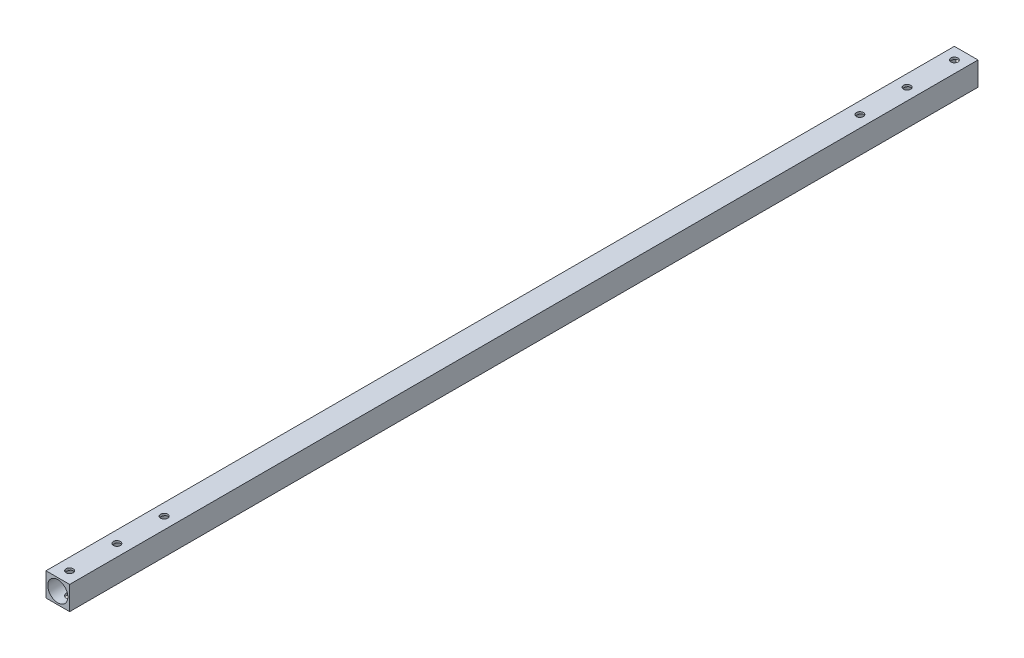
SolidWorks part; units mm, degrees
material "Thornel VCB-20 Carbon Cloth"
ref_plane "Front Plane" through (0, 0, 0) normal (0, 0, 1) x (1, 0, 0)
ref_plane "Top Plane" through (0, 0, 0) normal (0, 1, 0) x (1, 0, 0)
ref_plane "Right Plane" through (0, 0, 0) normal (1, 0, 0) x (0, 0, -1)
sketch "Sketch1" plane through (0, 0, 0) normal (0, 0, 1) x (1, 0, 0)
  line L1 (-5, -5) -> (5, -5)
  line L2 (-5, -5) -> (-5, 5)
  line L3 (-5, 5) -> (5, 5)
  line L4 (5, -5) -> (5, 5)
  line L5 (-5, -5) -> (5, 5) construction
  line L6 (-5, 5) -> (5, -5) construction
  circle A0 centre (0, 0) radius 4.25
  point P0 (0, 0)
  dimension "D3" = 8.5
  dimension "D1" = 10
  dimension "D2" = 10
extrude "Boss-Extrude1" add sketch "Sketch1" along normal blind 384.4
sketch "Sketch2" plane through (0, 5, 0) normal (0, 1, 0) x (1, 0, 0)
  line L0 (0, 0) -> (0, -5) construction
  line L1 (0, -5) -> (0, -25) construction
  line L2 (0, -25) -> (0, -45) construction
  line L3 (0, -384.4) -> (0, -379.4) construction
  line L4 (5, -384.4) -> (-5, -384.4) construction
  line L5 (0, -379.4) -> (0, -359.4) construction
  line L6 (0, -359.4) -> (0, -339.4) construction
  circle A0 centre (0, -5) radius 1.5
  circle A1 centre (0, -25) radius 1.5
  circle A2 centre (0, -45) radius 1.5
  circle A3 centre (0, -379.4) radius 1.5
  circle A4 centre (0, -359.4) radius 1.5
  circle A5 centre (0, -339.4) radius 1.5
  dimension "D3" = 3
  dimension "D4" = 5
  dimension "D6" = 3
  dimension "D1" = 5
  dimension "D2" = 20
  dimension "D5" = 20
extrude "Cut-Extrude1" cut sketch "Sketch2" against normal through all
